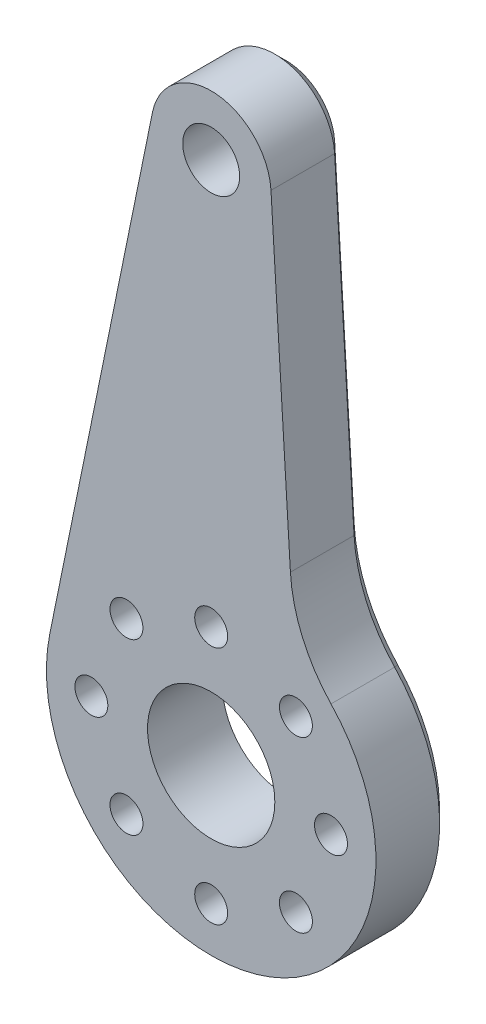
SolidWorks part; units mm, degrees
ref_plane "Front Plane" through (0, 0, 0) normal (0, 0, 1) x (1, 0, 0)
ref_plane "Top Plane" through (0, 0, 0) normal (0, 1, 0) x (1, 0, 0)
ref_plane "Right Plane" through (0, 0, 0) normal (1, 0, 0) x (0, 0, -1)
sketch "Sketch1" plane through (0, 0, 0) normal (0, 0, 1) x (1, 0, 0)
  line L0 (-18.855, 15.1761) -> (-25.7136, -18.4239)
  line L3 (-11.0167, 15.1761) -> (-4.1581, -18.4239)
  line L4 (-14.9359, 0.8298) -> (-14.9359, 20.8298) construction
  line L5 (-14.5846, -20.6239) -> (49985.4154, -20.6239) construction
  circle A2 centre (-14.9359, 14.3761) radius 1.9
  circle A3 centre (-14.9359, -20.6239) radius 4.25
  arc A5 (-11.0167, 15.1761) -> (-18.855, 15.1761) centre (-14.9359, 14.3761) ccw
  arc A6 (-25.7136, -18.4239) -> (-4.1581, -18.4239) centre (-14.9359, -20.6239) ccw
  circle A7 centre (-15.0314, -20.0888) radius 11 construction
  circle A8 centre (-6.9359, -20.6239) radius 1.1
  circle A9 centre (-9.279, -26.2808) radius 1.1
  circle A10 centre (-14.9359, -28.6239) radius 1.1
  circle A11 centre (-20.5927, -26.2808) radius 1.1
  circle A12 centre (-22.9359, -20.6239) radius 1.1
  circle A13 centre (-20.5927, -14.967) radius 1.1
  circle A14 centre (-14.9359, -12.6239) radius 1.1
  circle A15 centre (-9.279, -14.967) radius 1.1
  point P30 (-14.9359, -20.6239)
  dimension "D1" = 3.8
  dimension "D3" = 35
  dimension "D4" = 11
  dimension "D2" = 4
  dimension "D5" = 8.5
  dimension "D6" = 2.2
  dimension "D7" = 8
  dimension "D8" = 8
extrude "Boss-Extrude1" add sketch "Sketch1" along normal blind 5
sketch "Sketch2" plane through (0, 0, 5) normal (0, 0, 1) x (1, 0, 0)
  circle A0 centre (-14.9359, -20.6239) radius 11.5
  dimension "D1" = 23
extrude "Cut-Extrude1" [suppressed] cut sketch "Sketch2" against normal blind 1.75
sketch "Sketch5" plane through (0, 0, 5) normal (0, 0, 1) x (1, 0, 0)
  circle A2 centre (-14.8897, 3.8764) radius 1.55
  circle A3 centre (-14.8897, 3.8764) radius 8
extrude "Boss-Extrude2" [suppressed] add sketch "Sketch5" along normal blind 3
fillet "Fillet1" [suppressed] radius 1
sketch "Sketch4" plane through (0, 0, 0) normal (0, 0, -1) x (-1, 0, 0)
  circle A0 centre (22.9359, -20.6239) radius 1.75
  circle A1 centre (20.5927, -26.2808) radius 1.75
  circle A2 centre (14.9359, -28.6239) radius 1.75
  circle A3 centre (9.279, -26.2808) radius 1.75
  circle A4 centre (6.9359, -20.6239) radius 1.75
  circle A5 centre (9.279, -14.967) radius 1.75
  circle A6 centre (14.9359, -12.6239) radius 1.75
  circle A7 centre (20.5927, -14.967) radius 1.75
  circle A10 centre (14.9359, -20.6239) radius 4.25 construction
  point P20 (14.9359, -20.6239)
  dimension "D1" = 3.5
extrude "Cut-Extrude3" cut sketch "Sketch4" against normal blind 2.25
sketch "Croquis1" plane through (0, 0, 0) normal (0, 0, -1) x (-1, 0, 0)
  line L0 (10.9432, 14.6177) -> (9.3852, -11.127)
  line L1 (18.855, 15.1761) -> (25.7136, -18.4239) construction
  line L2 (11.0167, 15.1761) -> (4.1581, -18.4239)
  arc A0 (11.0167, 15.1761) -> (10.9432, 14.6177) centre (14.9359, 14.3761) ccw
  arc A1 (4.1581, -18.4239) -> (9.3852, -11.127) centre (14.9359, -20.6239) cw
  dimension "D1" = 15
extrude "Cortar-Extruir1" cut sketch "Croquis1" against normal blind 10
fillet "Redondeo1" radius 10 1 edges at (-9.3852, -11.127, 2.5)
chamfer "Chaflán1" distance 0.75 angle 45 5 edges at (-22.2843, -1.6239, 0) (-11.9214, -31.2028, 0) (-14.6543, 18.3662, 0) (-10.2947, 3.9023, 0) (-8.8417, -10.1814, 0)
